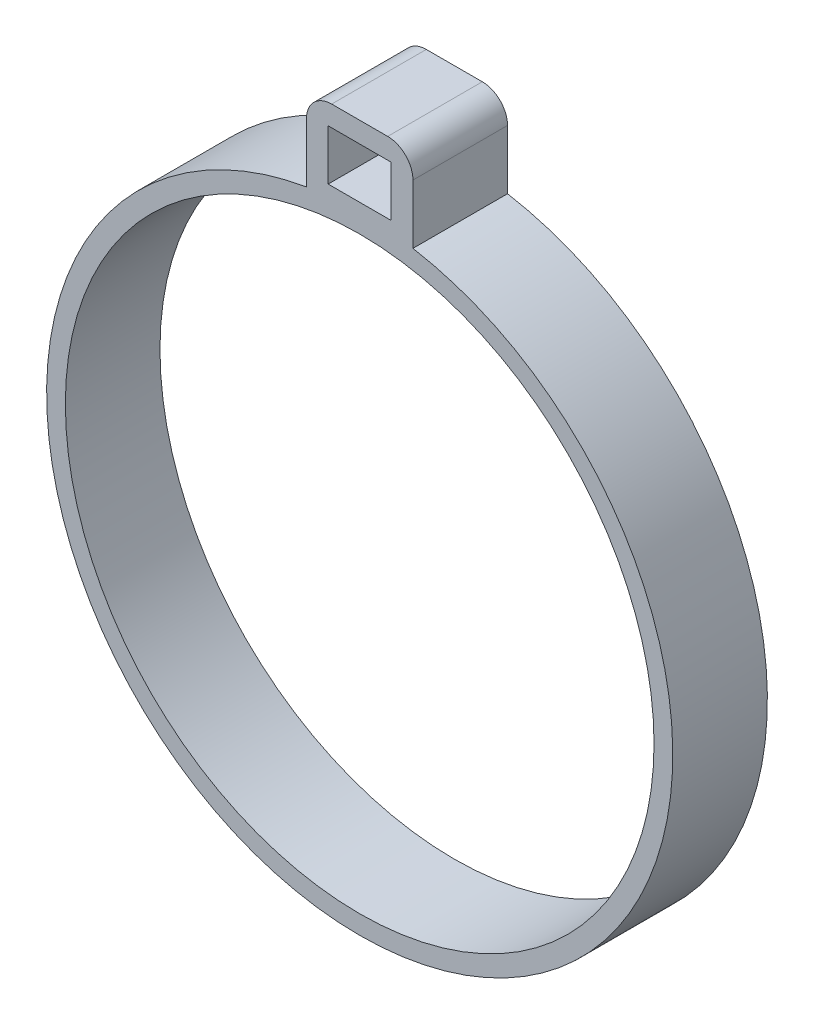
SolidWorks part; units mm, degrees
material "ABS PC"
ref_plane "Front Plane" through (0, 0, 0) normal (0, 0, 1) x (1, 0, 0)
ref_plane "Top Plane" through (0, 0, 0) normal (0, 1, 0) x (1, 0, 0)
ref_plane "Right Plane" through (0, 0, 0) normal (1, 0, 0) x (0, 0, -1)
sketch "Sketch1" plane through (0, 0, 0) normal (0, 0, 1) x (1, 0, 0)
  circle A0 centre (0, 0) radius 46.6677
  circle A1 centre (0, 0) radius 49.6385
extrude "Boss-Extrude1" add sketch "Sketch1" along normal mid plane 15
sketch "Sketch2" plane through (0, 0, -7.5) normal (0, 0, -1) x (-1, 0, 0)
  line L1 (-5, 59.0246) -> (5, 59.0246)
  line L2 (-5, 59.0246) -> (-5, 51.0246)
  line L3 (-5, 51.0246) -> (5, 51.0246)
  line L4 (5, 59.0246) -> (5, 51.0246)
  line L5 (-5, 59.0246) -> (5, 51.0246) construction
  line L6 (-5, 51.0246) -> (5, 59.0246) construction
  line L7 (-8.4397, 62.2912) -> (8.4397, 62.2912)
  line L8 (-8.4397, 62.2912) -> (-8.4397, 47.7581)
  line L9 (-8.4397, 47.7581) -> (8.4397, 47.7581)
  line L10 (8.4397, 62.2912) -> (8.4397, 47.7581)
  line L11 (-8.4397, 62.2912) -> (8.4397, 47.7581) construction
  line L12 (-8.4397, 47.7581) -> (8.4397, 62.2912) construction
  point P0 (0, 55.0246)
  point P5 (0, 55.0246)
  point P10 (0, 0)
  point P11 (0, 0)
  point P12 (0, 0)
  point P13 (0, 0)
  point P14 (-8.4397, 62.2912)
  dimension "D1" = 8
  dimension "D2" = 10
extrude "Boss-Extrude2" add sketch "Sketch2" against normal blind 15
fillet "Fillet1" radius 4 2 edges at (-8.4397, 62.2912, 0) (8.4397, 62.2912, 0)
